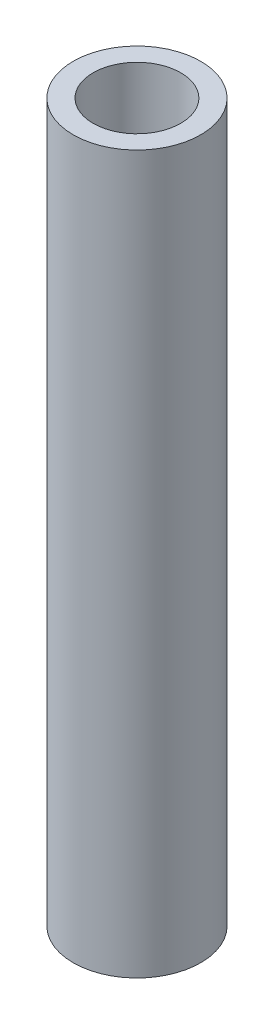
SolidWorks part; units mm, degrees
ref_plane "Ön Düzlem" through (0, 0, 0) normal (0, 0, 1) x (1, 0, 0)
ref_plane "Üst Düzlem" through (0, 0, 0) normal (0, 1, 0) x (1, 0, 0)
ref_plane "Sağ Düzlem" through (0, 0, 0) normal (1, 0, 0) x (0, 0, -1)
sketch "Sketch1" plane through (0, 0, 0) normal (0, 1, 0) x (1, 0, 0)
  circle A0 centre (0, 0) radius 40
  circle A1 centre (0, 0) radius 27.5
  dimension "D1" = 80
  dimension "D2" = 55
extrude "Boss-Extrude1" add sketch "Sketch1" along normal blind 450
